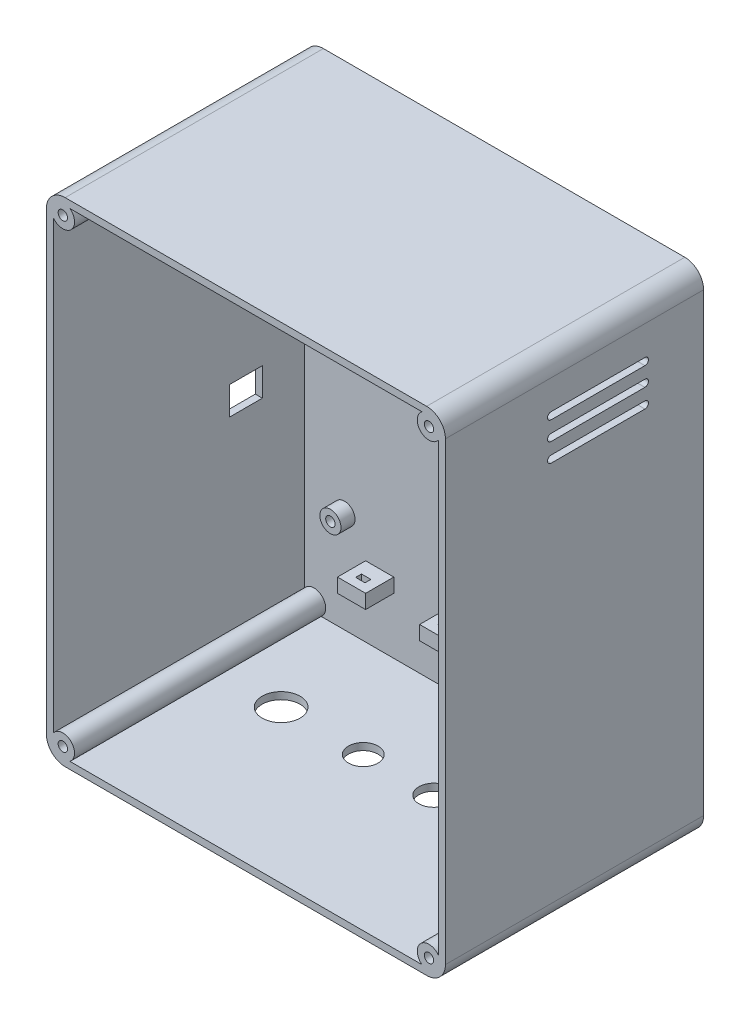
SolidWorks part; units mm, degrees
ref_plane "Front Plane" through (0, 0, 0) normal (0, 0, 1) x (1, 0, 0)
ref_plane "Top Plane" through (0, 0, 0) normal (0, 1, 0) x (1, 0, 0)
ref_plane "Right Plane" through (0, 0, 0) normal (1, 0, 0) x (0, 0, -1)
sketch "Sketch1" plane through (0, 0, 0) normal (0, 0, 1) x (1, 0, 0)
  line L0 (-77, 0) -> (77, 0)
  line L1 (85, 8) -> (85, 202)
  line L2 (77, 210) -> (-77, 210)
  line L3 (-85, 202) -> (-85, 8)
  arc A0 (-85, 8) -> (-77, 0) centre (-77, 8) ccw
  arc A1 (77, 0) -> (85, 8) centre (77, 8) ccw
  arc A2 (85, 202) -> (77, 210) centre (77, 202) ccw
  arc A3 (-77, 210) -> (-85, 202) centre (-77, 202) ccw
extrude "Block" add sketch "Sketch1" along normal blind 110
shell "Shell1" thickness 3
sketch "Sketch2" plane through (0, 0, 0) normal (0, 0, 1) x (1, 0, 0)
  circle A0 centre (-78, 7) radius 5
  circle A1 centre (78, 7) radius 5
  circle A2 centre (-78, 203) radius 5
  circle A3 centre (78, 203) radius 5
extrude "Corner columns" add sketch "Sketch2" along normal blind 110
ref_plane "P1_Front_110" through (0, 0, 110) normal (0, 0, 1) x (1, 0, 0)
sketch "Sketch3" plane through (0, 0, 110) normal (0, 0, 1) x (1, 0, 0)
  circle A0 centre (-78, 7) radius 2
  circle A1 centre (78, 7) radius 2
  circle A2 centre (-78, 203) radius 2
  circle A3 centre (78, 203) radius 2
extrude "Front panel insert holes" cut sketch "Sketch3" against normal blind 7
ref_plane "P2_Front_3" through (0, 0, 3) normal (0, 0, 1) x (1, 0, 0)
sketch "Sketch4" plane through (0, 0, 3) normal (0, 0, 1) x (1, 0, 0)
  circle A0 centre (-65, 46) radius 4.5
  circle A1 centre (65, 46) radius 4.5
  circle A2 centre (-65, 190) radius 4.5
  circle A3 centre (65, 190) radius 4.5
extrude "Plate bosses" add sketch "Sketch4" along normal blind 6
ref_plane "P3_Front_9" through (0, 0, 9) normal (0, 0, 1) x (1, 0, 0)
sketch "Sketch5" plane through (0, 0, 9) normal (0, 0, 1) x (1, 0, 0)
  circle A0 centre (-65, 46) radius 2
  circle A1 centre (65, 46) radius 2
  circle A2 centre (-65, 190) radius 2
  circle A3 centre (65, 190) radius 2
extrude "Plate insert holes" cut sketch "Sketch5" against normal blind 7
sketch "Sketch6" plane through (0, 0, 0) normal (0, 1, 0) x (1, 0, 0)
  circle A0 centre (-50, -45) radius 8.1
  circle A1 centre (-15, -45) radius 6.3
  circle A2 centre (15, -45) radius 6.3
  circle A3 centre (50, -45) radius 6.3
extrude "Cable gland holes" cut sketch "Sketch6" along normal blind 4
sketch "Sketch7" plane through (0, 0, 3) normal (0, 0, 1) x (1, 0, 0)
  line L1 (-56, 27) -> (-44, 27)
  line L2 (-56, 27) -> (-56, 33)
  line L3 (-56, 33) -> (-44, 33)
  line L4 (-44, 27) -> (-44, 33)
  line L5 (-56, 27) -> (-44, 33) construction
  line L6 (-56, 33) -> (-44, 27) construction
  line L7 (-21, 27) -> (-9, 27)
  line L8 (-21, 27) -> (-21, 33)
  line L9 (-21, 33) -> (-9, 33)
  line L10 (-9, 27) -> (-9, 33)
  line L11 (-21, 27) -> (-9, 33) construction
  line L12 (-21, 33) -> (-9, 27) construction
  line L13 (9, 27) -> (21, 27)
  line L14 (9, 27) -> (9, 33)
  line L15 (9, 33) -> (21, 33)
  line L16 (21, 27) -> (21, 33)
  line L17 (9, 27) -> (21, 33) construction
  line L18 (9, 33) -> (21, 27) construction
  line L19 (44, 27) -> (56, 27)
  line L20 (44, 27) -> (44, 33)
  line L21 (44, 33) -> (56, 33)
  line L22 (56, 27) -> (56, 33)
  line L23 (44, 27) -> (56, 33) construction
  line L24 (44, 33) -> (56, 27) construction
  point P0 (-50, 30)
  point P5 (-15, 30)
  point P10 (15, 30)
  point P15 (50, 30)
extrude "Cable tie bars" add sketch "Sketch7" along normal blind 12
ref_plane "P4_Top_26.99" through (0, 26.99, 0) normal (0, 1, 0) x (1, 0, 0)
sketch "Sketch8" plane through (0, 26.99, 0) normal (0, 1, 0) x (1, 0, 0)
  line L1 (-52, -11.25) -> (-48, -11.25)
  line L2 (-52, -11.25) -> (-52, -8.75)
  line L3 (-52, -8.75) -> (-48, -8.75)
  line L4 (-48, -11.25) -> (-48, -8.75)
  line L5 (-52, -11.25) -> (-48, -8.75) construction
  line L6 (-52, -8.75) -> (-48, -11.25) construction
  line L7 (-17, -11.25) -> (-13, -11.25)
  line L8 (-17, -11.25) -> (-17, -8.75)
  line L9 (-17, -8.75) -> (-13, -8.75)
  line L10 (-13, -11.25) -> (-13, -8.75)
  line L11 (-17, -11.25) -> (-13, -8.75) construction
  line L12 (-17, -8.75) -> (-13, -11.25) construction
  line L13 (13, -11.25) -> (17, -11.25)
  line L14 (13, -11.25) -> (13, -8.75)
  line L15 (13, -8.75) -> (17, -8.75)
  line L16 (17, -11.25) -> (17, -8.75)
  line L17 (13, -11.25) -> (17, -8.75) construction
  line L18 (13, -8.75) -> (17, -11.25) construction
  line L19 (48, -11.25) -> (52, -11.25)
  line L20 (48, -11.25) -> (48, -8.75)
  line L21 (48, -8.75) -> (52, -8.75)
  line L22 (52, -11.25) -> (52, -8.75)
  line L23 (48, -11.25) -> (52, -8.75) construction
  line L24 (48, -8.75) -> (52, -11.25) construction
  point P0 (-50, -10)
  point P5 (-15, -10)
  point P10 (15, -10)
  point P15 (50, -10)
extrude "Cable tie slots" cut sketch "Sketch8" along normal blind 6.02
ref_plane "P5_Right_-85" through (-85, 0, 0) normal (1, 0, 0) x (0, 0, -1)
sketch "Sketch9" plane through (-85, 0, 0) normal (1, 0, 0) x (0, 0, -1)
  line L1 (-35, 89) -> (-21, 89)
  line L2 (-35, 89) -> (-35, 101)
  line L3 (-35, 101) -> (-21, 101)
  line L4 (-21, 89) -> (-21, 101)
  line L5 (-35, 89) -> (-21, 101) construction
  line L6 (-35, 101) -> (-21, 89) construction
  point P0 (-28, 95)
extrude "USB access" cut sketch "Sketch9" along normal blind 4
ref_plane "P6_Right_-85" through (-85, 0, 0) normal (1, 0, 0) x (0, 0, -1)
sketch "Sketch10" plane through (-85, 0, 0) normal (1, 0, 0) x (0, 0, -1)
  line L0 (-25, 172) -> (-65, 172) construction
  line L1 (-25, 170.5) -> (-65, 170.5)
  line L2 (-25, 173.5) -> (-65, 173.5)
  line L3 (-25, 180) -> (-65, 180) construction
  line L4 (-25, 178.5) -> (-65, 178.5)
  line L5 (-25, 181.5) -> (-65, 181.5)
  line L6 (-25, 188) -> (-65, 188) construction
  line L7 (-25, 186.5) -> (-65, 186.5)
  line L8 (-25, 189.5) -> (-65, 189.5)
  arc A0 (-25, 170.5) -> (-25, 173.5) centre (-25, 172) ccw
  arc A1 (-65, 173.5) -> (-65, 170.5) centre (-65, 172) ccw
  arc A2 (-25, 178.5) -> (-25, 181.5) centre (-25, 180) ccw
  arc A3 (-65, 181.5) -> (-65, 178.5) centre (-65, 180) ccw
  arc A4 (-25, 186.5) -> (-25, 189.5) centre (-25, 188) ccw
  arc A5 (-65, 189.5) -> (-65, 186.5) centre (-65, 188) ccw
  point P2 (-45, 172)
  point P7 (-45, 180)
  point P14 (-45, 188)
  point P21 (0, 0)
extrude "Vents left" cut sketch "Sketch10" along normal blind 4
ref_plane "P7_Right_85" through (85, 0, 0) normal (1, 0, 0) x (0, 0, -1)
sketch "Sketch11" plane through (85, 0, 0) normal (1, 0, 0) x (0, 0, -1)
  line L0 (-25, 172) -> (-65, 172) construction
  line L1 (-25, 170.5) -> (-65, 170.5)
  line L2 (-25, 173.5) -> (-65, 173.5)
  line L3 (-25, 180) -> (-65, 180) construction
  line L4 (-25, 178.5) -> (-65, 178.5)
  line L5 (-25, 181.5) -> (-65, 181.5)
  line L6 (-25, 188) -> (-65, 188) construction
  line L7 (-25, 186.5) -> (-65, 186.5)
  line L8 (-25, 189.5) -> (-65, 189.5)
  arc A0 (-25, 170.5) -> (-25, 173.5) centre (-25, 172) ccw
  arc A1 (-65, 173.5) -> (-65, 170.5) centre (-65, 172) ccw
  arc A2 (-25, 178.5) -> (-25, 181.5) centre (-25, 180) ccw
  arc A3 (-65, 181.5) -> (-65, 178.5) centre (-65, 180) ccw
  arc A4 (-25, 186.5) -> (-25, 189.5) centre (-25, 188) ccw
  arc A5 (-65, 189.5) -> (-65, 186.5) centre (-65, 188) ccw
  point P2 (-45, 172)
  point P7 (-45, 180)
  point P14 (-45, 188)
  point P21 (0, 0)
extrude "Vents right" cut sketch "Sketch11" against normal blind 4
sketch "Sketch12" plane through (0, 0, 0) normal (0, 0, 1) x (1, 0, 0)
  circle A0 centre (-45, 165) radius 4.75
  circle A1 centre (45, 165) radius 4.75
extrude "Keyhole heads" cut sketch "Sketch12" along normal blind 4
sketch "Sketch13" plane through (0, 0, 0) normal (0, 0, 1) x (1, 0, 0)
  line L0 (-45, 165) -> (-45, 176) construction
  line L1 (-47.4, 165) -> (-47.4, 176)
  line L2 (-42.6, 165) -> (-42.6, 176)
  line L3 (45, 165) -> (45, 176) construction
  line L4 (42.6, 165) -> (42.6, 176)
  line L5 (47.4, 165) -> (47.4, 176)
  arc A0 (-47.4, 165) -> (-42.6, 165) centre (-45, 165) ccw
  arc A1 (-42.6, 176) -> (-47.4, 176) centre (-45, 176) ccw
  arc A2 (42.6, 165) -> (47.4, 165) centre (45, 165) ccw
  arc A3 (47.4, 176) -> (42.6, 176) centre (45, 176) ccw
  point P2 (-45, 170.5)
  point P7 (45, 170.5)
  point P14 (0, 0)
extrude "Keyhole slots" cut sketch "Sketch13" along normal blind 4
